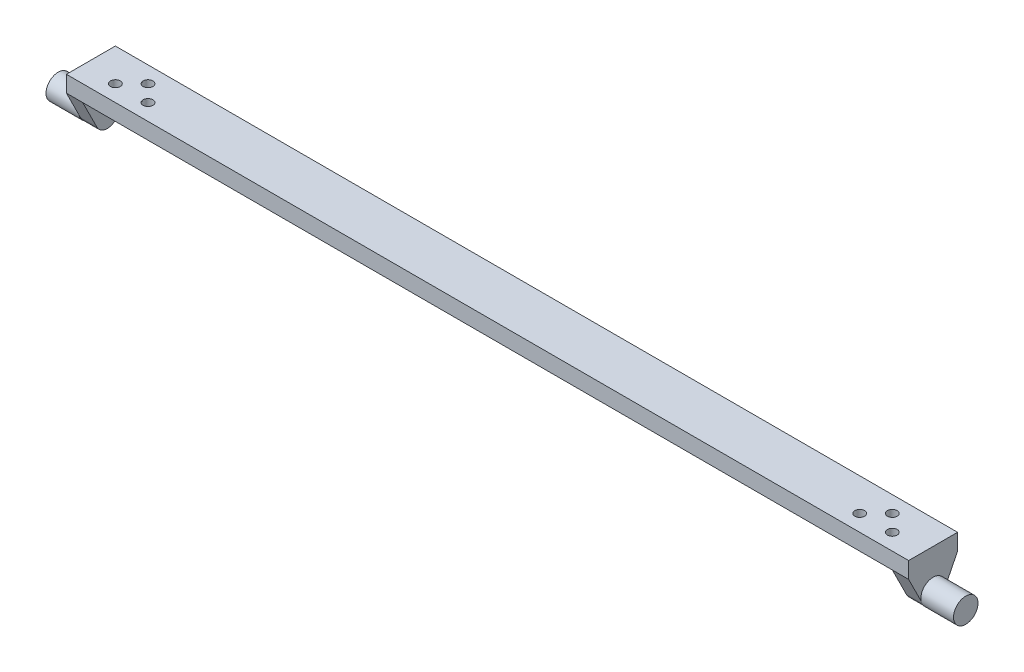
SolidWorks part; units mm, degrees
ref_plane "Front Plane" through (0, 0, 0) normal (0, 0, 1) x (1, 0, 0)
ref_plane "Top Plane" through (0, 0, 0) normal (0, 1, 0) x (1, 0, 0)
ref_plane "Right Plane" through (0, 0, 0) normal (1, 0, 0) x (0, 0, -1)
sketch "Sketch1" plane through (0, 0, 0) normal (0, 1, 0) x (1, 0, 0)
  line L0 (-47.3881, 0.3343) -> (-47.3881, -14.6657)
  line L1 (-47.3881, -14.6657) -> (200.6119, -14.6657)
  line L2 (200.6119, -14.6657) -> (200.6119, 0.3343)
  line L3 (200.6119, 0.3343) -> (-47.3881, 0.3343)
  dimension "D1" = 15
  dimension "D2" = 15
  dimension "D3" = 248
extrude "Boss-Extrude1" add sketch "Sketch1" along normal blind 5
sketch "Sketch2" plane through (0, 5, 0) normal (0, 1, 0) x (1, 0, 0)
  line L0 (-47.3881, 0.3343) -> (-47.3881, -14.6657) construction
  line L1 (-47.3881, -14.6657) -> (200.6119, -14.6657) construction
  line L2 (200.6119, 0.3343) -> (-47.3881, 0.3343) construction
  line L3 (200.6119, -14.6657) -> (200.6119, 0.3343) construction
  circle A0 centre (-42.3881, -9.6657) radius 1.5
  circle A1 centre (-37.3881, -4.6657) radius 1.5
  circle A2 centre (-32.3881, -9.6657) radius 1.5
  circle A3 centre (185.6119, -9.6657) radius 1.5
  circle A4 centre (190.6119, -4.6657) radius 1.5
  circle A5 centre (195.6119, -9.6657) radius 1.5
  dimension "D1" = 3
  dimension "D2" = 3
  dimension "D3" = 3
  dimension "D4" = 5
  dimension "D5" = 5
  dimension "D6" = 10
  dimension "D7" = 5
  dimension "D8" = 15
  dimension "D9" = 5
  dimension "D10" = 3
  dimension "D11" = 3
  dimension "D12" = 3
  dimension "D13" = 5
  dimension "D14" = 5
  dimension "D15" = 5
  dimension "D16" = 10
  dimension "D17" = 15
  dimension "D18" = 5
extrude "Cut-Extrude1" cut sketch "Sketch2" against normal blind 5
sketch "Sketch3" plane through (200.6119, 0, 0) normal (1, 0, 0) x (0, 0, -1)
  line L0 (0.3343, 0) -> (0.3343, 5)
  line L1 (0.3343, 5) -> (-14.6657, 5)
  line L2 (-14.6657, 5) -> (-14.6657, 0)
  line L3 (-14.6657, 0) -> (-7.1657, -15)
  line L4 (-7.1657, -15) -> (0.3343, 0)
  line L5 (-14.6657, 0) -> (0.3343, 0) construction
  dimension "D1" = 15
extrude "Boss-Extrude2" add sketch "Sketch3" along normal blind 5
fillet "Fillet1" radius 3.5 1 edges at (203.1119, -15, 7.1657)
sketch "Sketch4" plane through (205.6119, 0, 0) normal (1, 0, 0) x (0, 0, -1)
  line L0 (0.3343, 5) -> (-14.6657, 5) construction
  circle A0 centre (-7.1657, -6.9238) radius 3.75
  arc A1 (-10.2962, -8.739) -> (-4.0352, -8.739) centre (-7.1657, -7.1738) ccw construction
  point P2 (-7.1657, 5)
  point P5 (-7.1657, -10.6738)
  dimension "D1" = 7.5
  dimension "D2" = 0
  dimension "D3" = 3.75
extrude "Boss-Extrude3" add sketch "Sketch4" along normal blind 10
sketch "Sketch5" plane through (-47.3881, 0, 0) normal (-1, 0, 0) x (0, 0, 1)
  line L0 (-0.3343, 0) -> (-0.3343, 5)
  line L1 (-0.3343, 5) -> (14.6657, 5)
  line L2 (14.6657, 5) -> (14.6657, 0)
  line L3 (14.6657, 5) -> (14.6657, 0) construction
  line L4 (14.6657, 0) -> (7.1657, -15)
  line L5 (7.1657, -15) -> (-0.3343, 0)
  line L6 (-0.3343, 0) -> (14.6657, 0) construction
  dimension "D1" = 15
extrude "Boss-Extrude4" add sketch "Sketch5" along normal blind 5
fillet "Fillet2" radius 3.5 1 edges at (-49.8881, -15, 7.1657)
sketch "Sketch6" plane through (-52.3881, 0, 0) normal (-1, 0, 0) x (0, 0, 1)
  circle A0 centre (7.1657, -6.9238) radius 3.75
  arc A2 (4.0352, -8.739) -> (10.2962, -8.739) centre (7.1657, -7.1738) ccw construction
  point P2 (7.1657, -10.6738)
  dimension "D1" = 7.5
  dimension "D2" = 3.75
extrude "Boss-Extrude5" add sketch "Sketch6" along normal blind 10
